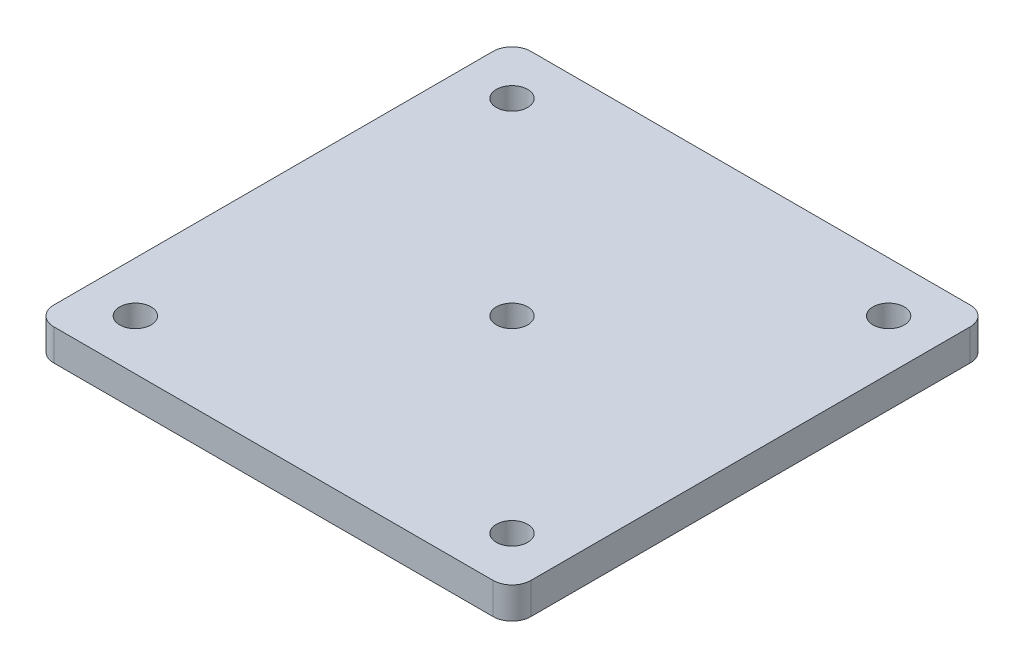
SolidWorks part; units mm, degrees
ref_plane "Front Plane" through (0, 0, 0) normal (0, 0, 1) x (1, 0, 0)
ref_plane "Top Plane" through (0, 0, 0) normal (0, 1, 0) x (1, 0, 0)
ref_plane "Right Plane" through (0, 0, 0) normal (1, 0, 0) x (0, 0, -1)
sketch "Sketch1" plane through (0, 0, 0) normal (0, 1, 0) x (1, 0, 0)
  line L1 (-35, -38) -> (35, -38)
  line L2 (-38, -35) -> (-38, 35)
  line L3 (-35, 38) -> (35, 38)
  line L4 (38, -35) -> (38, 35)
  line L5 (-38, -38) -> (38, 38) construction
  line L6 (-38, 38) -> (38, -38) construction
  arc A0 (35, 38) -> (38, 35) centre (35, 35) cw
  arc A1 (38, -35) -> (35, -38) centre (35, -35) cw
  arc A2 (-35, -38) -> (-38, -35) centre (-35, -35) cw
  arc A3 (-38, 35) -> (-35, 38) centre (-35, 35) cw
  circle A4 centre (0, 0) radius 2.5
  circle A5 centre (-30, -30) radius 2.5
  circle A6 centre (-30, 30) radius 2.5
  circle A7 centre (30, 30) radius 2.5
  circle A8 centre (30, -30) radius 2.5
  point P0 (0, 0)
  point P22 (0, 0)
  point P31 (0, 0)
  dimension "D2" = 3
  dimension "D3" = 5
  dimension "D5" = 60
  dimension "D1" = 76
  dimension "D4" = 4
extrude "Boss-Extrude1" add sketch "Sketch1" along normal blind 5
